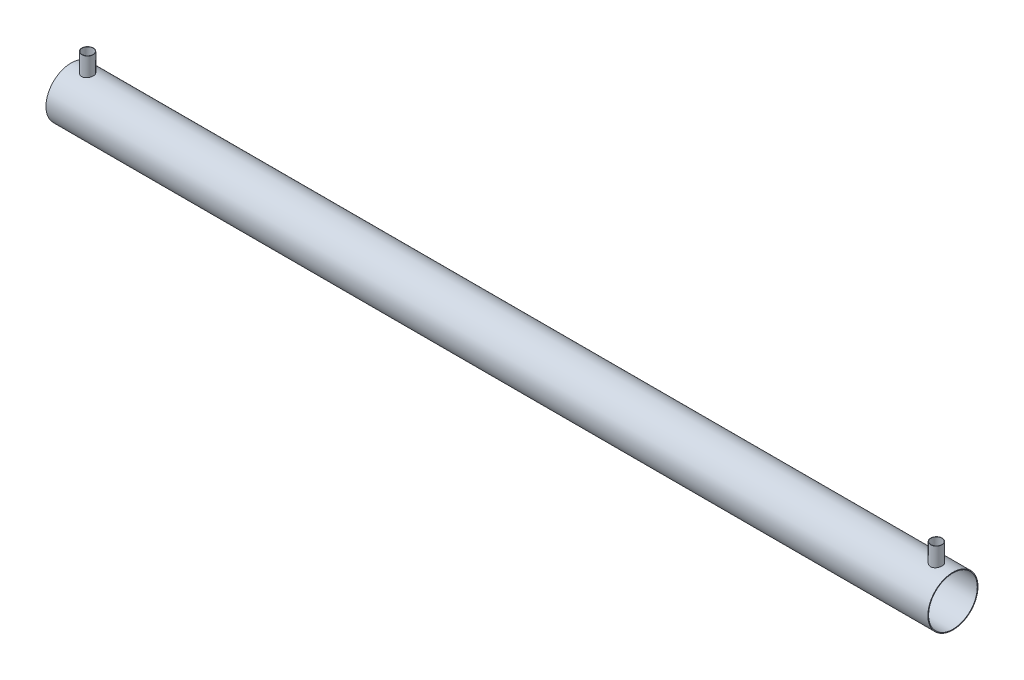
SolidWorks part; units mm, degrees
ref_plane "Front Plane" through (0, 0, 0) normal (0, 0, 1) x (1, 0, 0)
ref_plane "Top Plane" through (0, 0, 0) normal (0, 1, 0) x (1, 0, 0)
ref_plane "Right Plane" through (0, 0, 0) normal (1, 0, 0) x (0, 0, -1)
sketch "Sketch1" plane through (0, 0, 0) normal (1, 0, 0) x (0, 0, -1)
  circle A0 centre (0, 0) radius 173.275
  circle A1 centre (0, 0) radius 168.275
  dimension "D1" = 346.55
  dimension "D2" = 336.55
extrude "Boss-Extrude1" add sketch "Sketch1" along normal blind 6096
ref_plane "Plane1" through (0, 300.275, 0) normal (0, 1, 0) x (1, 0, 0)
sketch "Sketch3" plane through (0, 300.275, 0) normal (0, 1, 0) x (1, 0, 0)
  line L0 (0, 0) -> (114.3, 0) construction
  line L1 (6096, 0) -> (5981.7, 0) construction
  line L2 (6096, -173.275) -> (6096, 173.275) construction
  circle A0 centre (114.3, 0) radius 40.1
  circle A1 centre (5981.7, 0) radius 40.1
  dimension "D2" = 80.2
  dimension "D4" = 80.2
  dimension "D1" = 114.3
  dimension "D3" = 114.3
extrude "Boss-Extrude2" add sketch "Sketch3" against normal up to surface (131.7039 mm away)
sketch "Sketch4" plane through (0, 300.275, 0) normal (0, 1, 0) x (1, 0, 0)
  circle A0 centre (114.3, 0) radius 38.1
  circle A1 centre (5981.7, 0) radius 38.1
  dimension "D1" = 76.2
  dimension "D2" = 76.2
extrude "Cut-Extrude1" cut sketch "Sketch4" against normal up to next
